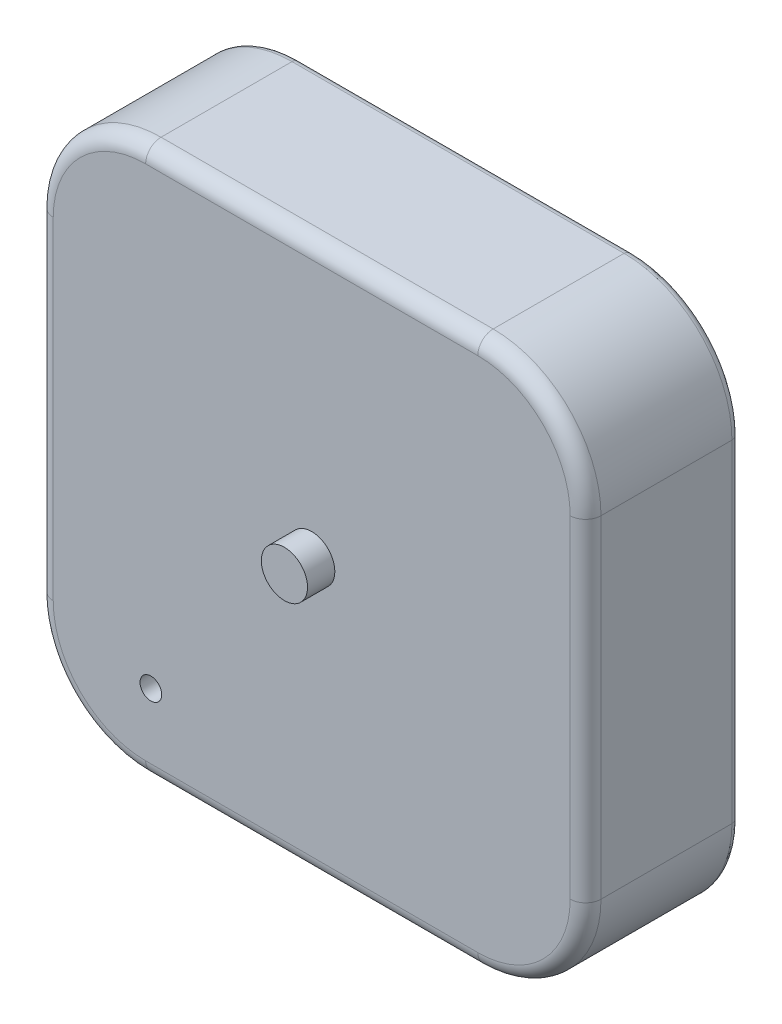
SolidWorks part; units mm, degrees
material "Plain Carbon Steel"
ref_plane "Front Plane" through (0, 0, 0) normal (0, 0, 1) x (1, 0, 0)
ref_plane "Top Plane" through (0, 0, 0) normal (0, 1, 0) x (1, 0, 0)
ref_plane "Right Plane" through (0, 0, 0) normal (1, 0, 0) x (0, 0, -1)
sketch "Sketch1" plane through (0, 0, 0) normal (0, 0, 1) x (1, 0, 0)
  line L1 (-177.8, 177.8) -> (177.8, 177.8)
  line L2 (-177.8, 177.8) -> (-177.8, -177.8)
  line L3 (-177.8, -177.8) -> (177.8, -177.8)
  line L4 (177.8, 177.8) -> (177.8, -177.8)
  line L5 (-177.8, 177.8) -> (177.8, -177.8) construction
  line L6 (-177.8, -177.8) -> (177.8, 177.8) construction
  point P0 (0, 0)
  dimension "D1" = 355.6
  dimension "D2" = 355.6
extrude "Boss-Extrude1" add sketch "Sketch1" along normal blind 100
fillet "Fillet1" radius 70 4 edges at (177.8, 177.8, 50) (177.8, -177.8, 50) (-177.8, -177.8, 50) (-177.8, 177.8, 50)
sketch "Sketch2" plane through (0, 0, 100) normal (0, 0, 1) x (1, 0, 0)
  line L0 (-177.8, 107.8) -> (-177.8, -107.8) construction
  line L1 (-107.8, -177.8) -> (107.8, -177.8) construction
  circle A0 centre (-104.42, -125.46) radius 7.03
  dimension "D1" = 14.06
  dimension "D2" = 73.38
  dimension "D3" = 52.34
extrude "Cut-Extrude1" cut sketch "Sketch2" against normal blind 25.04
fillet "Fillet3" radius 5 8 edges at (-157.2975, -157.2975, 0) (-177.8, 0, 0) (-157.2975, 157.2975, 0) (0, 177.8, 0) (157.2975, 157.2975, 0) (177.8, 0, 0) (157.2975, -157.2975, 0) (0, -177.8, 0)
fillet "Fillet4" radius 10 8 edges at (-157.2975, -157.2975, 100) (-177.8, 0, 100) (-157.2975, 157.2975, 100) (0, 177.8, 100) (157.2975, 157.2975, 100) (177.8, 0, 100) (157.2975, -157.2975, 100) (0, -177.8, 100)
sketch "Sketch3" plane through (0, 0, 100) normal (0, 0, 1) x (1, 0, 0)
  circle A0 centre (0, 0) radius 15
  dimension "D1" = 30
extrude "Boss-Extrude2" add sketch "Sketch3" along normal blind 17.7
